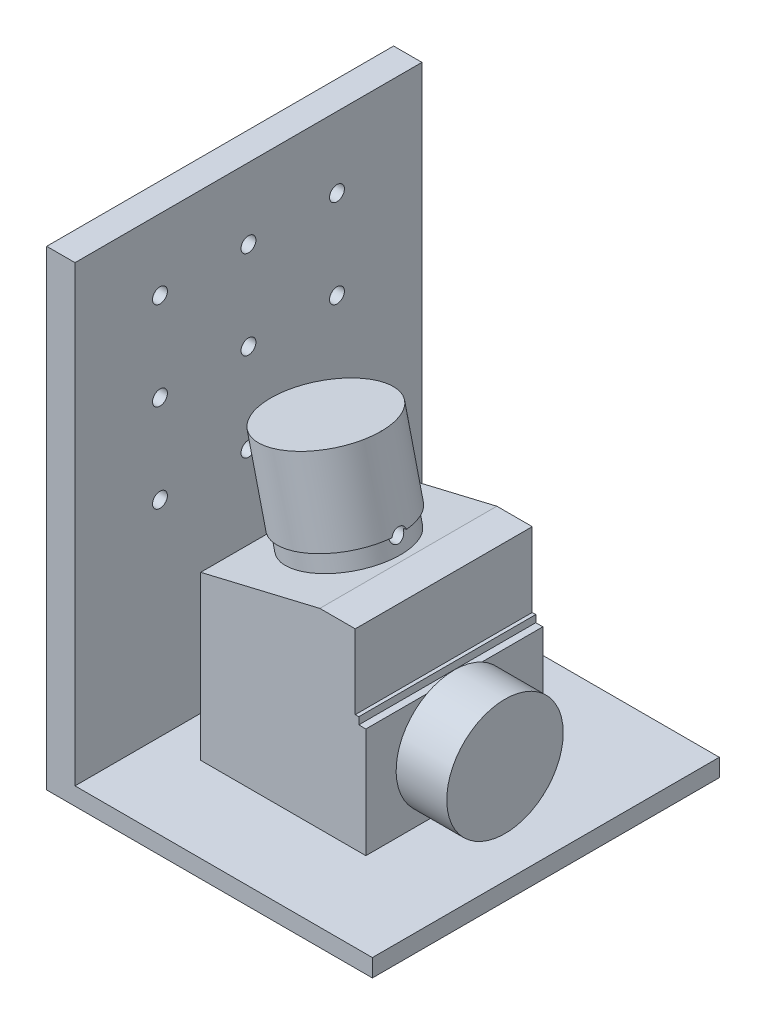
SolidWorks part; units mm, degrees
material "1.4511 (X3CrNb17)"
ref_plane "前视基准面" through (0, 0, 0) normal (0, 0, 1) x (1, 0, 0)
ref_plane "上视基准面" through (0, 0, 0) normal (0, 1, 0) x (1, 0, 0)
ref_plane "右视基准面" through (0, 0, 0) normal (1, 0, 0) x (0, 0, -1)
sketch "草图1" plane through (0, 0, 0) normal (0, 0, 1) x (1, 0, 0)
  line L0 (0, 0) -> (0, 133)
  line L1 (0, 133) -> (8, 133)
  line L2 (8, 133) -> (8, 5)
  line L3 (8, 5) -> (92, 5)
  line L4 (92, 5) -> (92, 0)
  line L5 (92, 0) -> (0, 0)
  dimension "D1" = 133
  dimension "D2" = 8
  dimension "D3" = 128
  dimension "D4" = 84
extrude "凸台-拉伸1" add sketch "草图1" along normal blind 98
ref_plane "基准面1" through (0, 0, 49) normal (0, 0, 1) x (1, 0, 0)
sketch "草图2" plane through (0, 0, 49) normal (0, 0, 1) x (1, 0, 0)
  line L4 (66.16, 36) -> (64.16, 36)
  line L5 (64.16, 36) -> (64.16, 38)
  line L6 (64.16, 38) -> (63.16, 38)
  line L7 (63.16, 38) -> (63.16, 59)
  line L8 (63.16, 59) -> (53.16, 59)
  line L9 (19.5, 5) -> (19.5, 51)
  line L10 (19.5, 51) -> (53.16, 59)
  line L14 (66.16, 36) -> (66.16, 5)
  line L15 (19.5, 5) -> (66.16, 5)
  dimension "D5" = 2
  dimension "D6" = 2
  dimension "D7" = 1
  dimension "D8" = 21
  dimension "D9" = 10
  dimension "D10" = 46
extrude "凸台-拉伸2" add sketch "草图2" along normal mid plane 50 separate body
sketch "草图4" plane through (66.16, 0, 0) normal (1, 0, 0) x (0, 0, -1)
  line L0 (-49, 38) -> (-49, 5) construction
  line L1 (-74, 38) -> (-24, 38) construction
  line L2 (-98, 5) -> (0, 5) construction
  circle A0 centre (-49, 21.5) radius 16.45
  dimension "D1" = 32.9
extrude "凸台-拉伸6" add sketch "草图4" along normal blind 14.3
sketch "草图5" plane through (-10.4305, 43.8864, 0) normal (-0.2312, 0.9729, 0) x (0.9729, 0.2312, 0)
  circle A0 centre (48.0631, -49) radius 15
  dimension "D1" = 30
extrude "凸台-拉伸7" add sketch "草图5" along normal blind 5
sketch "草图6" plane through (-11.5867, 48.7509, 0) normal (-0.2312, 0.9729, 0) x (0.9729, 0.2312, 0)
  circle A0 centre (48.0631, -49) radius 16
extrude "凸台-拉伸8" add sketch "草图6" along normal blind 23
sketch "草图7" plane through (0, 0, 24) normal (0, 0, -1) x (-1, 0, 0)
  line L0 (-66.16, 5) -> (-66.16, 36) construction
  line L1 (-19.5, 5) -> (-66.16, 5) construction
  circle A0 centre (-50.16, 21) radius 5
  point P2 (0, 0)
  dimension "D1" = 10
  dimension "D2" = 16
  dimension "D3" = 16
extrude "切除-拉伸2" cut sketch "草图7" against normal blind 5
sketch "草图8" plane through (0, 0, 0) normal (-1, 0, 0) x (0, 0, 1)
  line L0 (98, 133) -> (0, 133) construction
  line L1 (24, 113) -> (74, 113) construction
  line L2 (24, 113) -> (24, 63) construction
  line L3 (24, 63) -> (74, 63) construction
  line L4 (74, 113) -> (74, 63) construction
  line L5 (24, 113) -> (74, 63) construction
  line L6 (24, 63) -> (74, 113) construction
  line L7 (98, 133) -> (98, 0) construction
  line L8 (24, 88) -> (74, 88) construction
  line L9 (49, 63) -> (49, 113) construction
  point P0 (49, 88)
  dimension "D1" = 50
  dimension "D2" = 50
  dimension "D3" = 20
  dimension "D4" = 24
hole_wizard "M5 螺纹孔1" positions "草图9" profile "草图10" tap size "M5" standard "GB" end condition through all
sketch "草图9" plane through (0, 0, 0) normal (-1, 0, 0) x (0, 0, 1)
  line L0 (24, 113) -> (74, 63) construction
  point P0 (24, 63)
  point P3 (49, 63)
  point P6 (74, 63)
  point P9 (74, 88)
  point P12 (49, 88)
  point P16 (24, 88)
  point P19 (24, 113)
  point P22 (49, 113)
  point P25 (74, 113)
sketch "草图10" plane through (0, 63, 24) normal (0, 1, 0) x (0, 0, 1)
  line L0 (0, 0) -> (0, 92)
  line L1 (0, 92) -> (2.1, 92)
  line L2 (2.1, 92) -> (2.1, 0)
  line L5 (2.1, 0) -> (0, 0)
  line L11 (0, -6.35) -> (0, 107.95) construction
  dimension "通孔螺纹孔钻头直径" = 4.2
  dimension "通孔螺纹孔钻头深度" = 92
cosmetic thread "孔螺蚊线1" parameters "D2"=5
cosmetic thread "孔螺蚊线2" parameters "D2"=5
cosmetic thread "孔螺蚊线3" parameters "D2"=5
cosmetic thread "孔螺蚊线4" parameters "D2"=5
cosmetic thread "孔螺蚊线5" parameters "D2"=5
cosmetic thread "孔螺蚊线6" parameters "D2"=5
cosmetic thread "孔螺蚊线7" parameters "D2"=5
cosmetic thread "孔螺蚊线8" parameters "D2"=5
cosmetic thread "孔螺蚊线9" parameters "D2"=5
